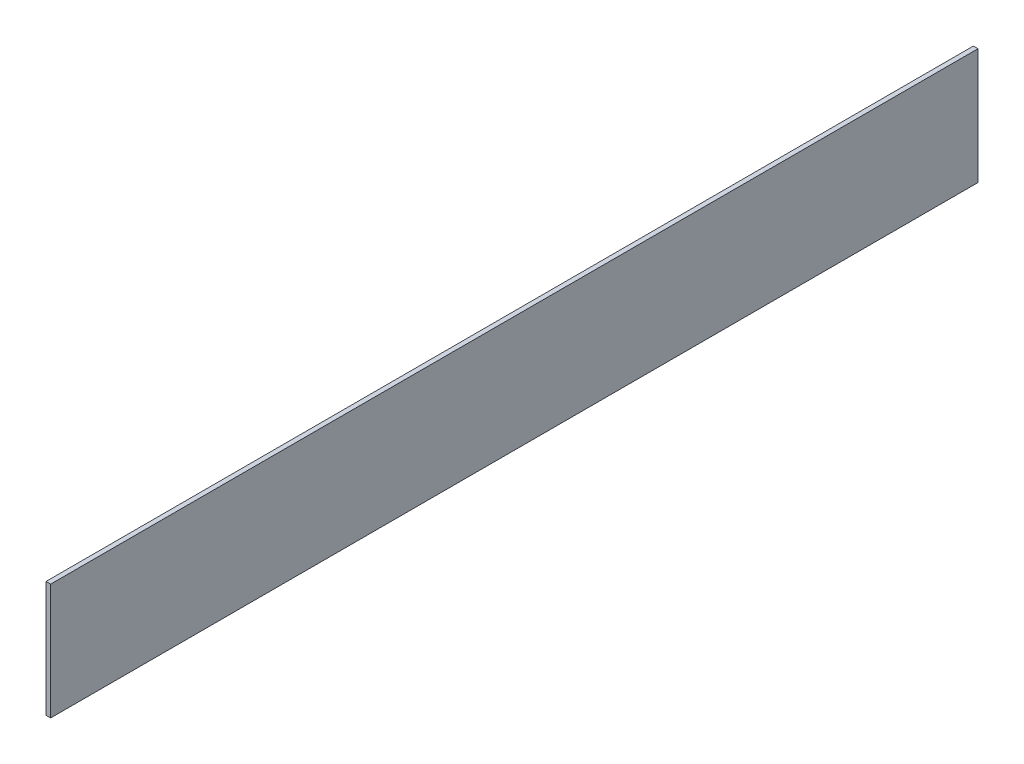
SolidWorks part; units mm, degrees
ref_plane "Front Plane" through (0, 0, 0) normal (0, 0, 1) x (1, 0, 0)
ref_plane "Top Plane" through (0, 0, 0) normal (0, 1, 0) x (1, 0, 0)
ref_plane "Right Plane" through (0, 0, 0) normal (1, 0, 0) x (0, 0, -1)
other "Configuration Table"
sketch "Sketch1" plane through (0, 0, 0) normal (0, 0, 1) x (1, 0, 0)
  line L1 (318.4, 1.6) -> (320, 1.6)
  line L2 (318.4, 1.6) -> (318.4, 41.6)
  line L3 (318.4, 41.6) -> (320, 41.6)
  line L4 (320, 1.6) -> (320, 41.6)
extrude "KUTU_duvar_sag_1" add sketch "Sketch1" against normal blind 320 separate body
